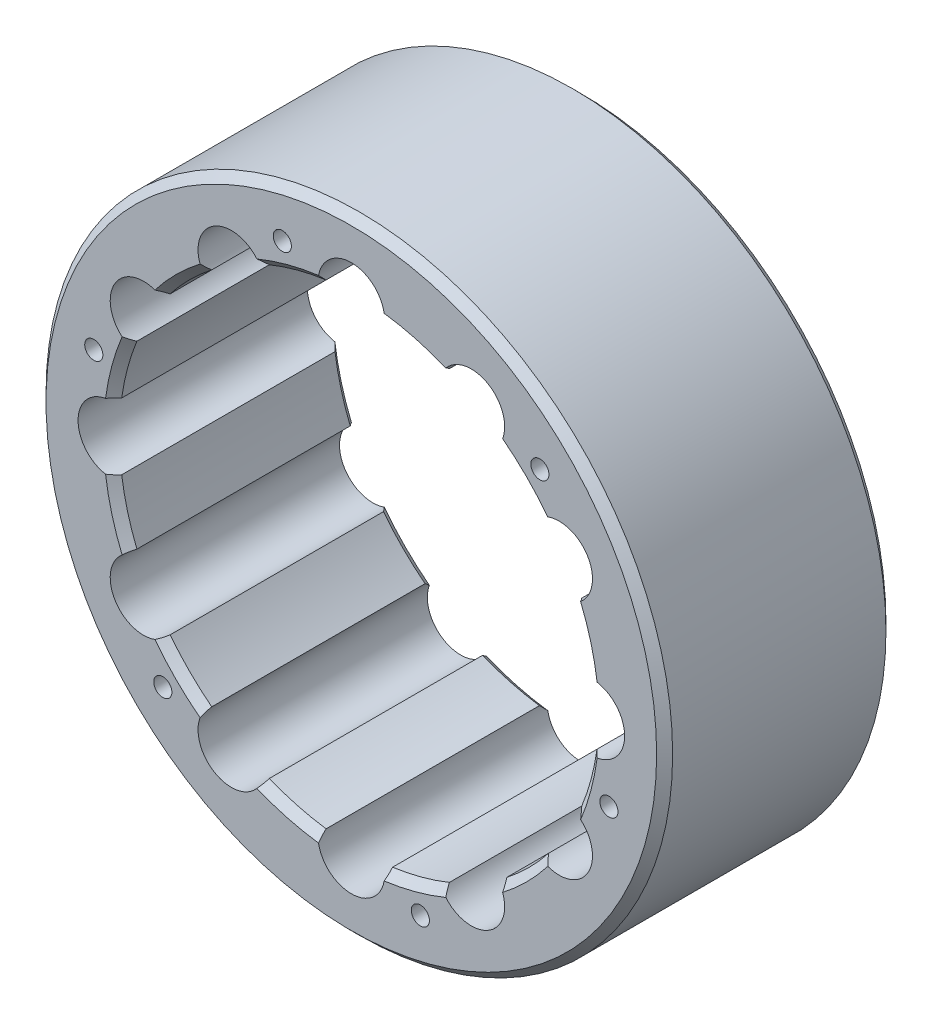
SolidWorks part; units mm, degrees
ref_plane "前视" through (0, 0, 0) normal (0, 0, 1) x (1, 0, 0)
ref_plane "上视" through (0, 0, 0) normal (0, 1, 0) x (1, 0, 0)
ref_plane "右视" through (0, 0, 0) normal (1, 0, 0) x (0, 0, -1)
sketch "草图1" plane through (0, 0, 0) normal (0, 0, 1) x (1, 0, 0)
  circle A0 centre (0, 0) radius 117.5
  circle A1 centre (0, 0) radius 90
  dimension "D1" = 235
  dimension "D2" = 180
extrude "凸台-拉伸1" add sketch "草图1" along normal blind 86
chamfer "倒角1" distance 3 angle 45 4 edges at (90, 0, 0) (117.5, 0, 0) (117.5, 0, 86) (90, 0, 86)
sketch "草图2" plane through (0, 0, 86) normal (0, 0, 1) x (1, 0, 0)
  line L0 (0, 0) -> (0, 203.5148) construction
  circle A0 centre (0, 90) radius 12.5
  circle A1 centre (0, 0) radius 90 construction
  circle A2 centre (45, 77.9423) radius 12.5
  circle A3 centre (77.9423, 45) radius 12.5
  circle A4 centre (90, 0) radius 12.5
  circle A5 centre (77.9423, -45) radius 12.5
  circle A6 centre (45, -77.9423) radius 12.5
  circle A7 centre (0, -90) radius 12.5
  circle A8 centre (-45, -77.9423) radius 12.5
  circle A9 centre (-77.9423, -45) radius 12.5
  circle A10 centre (-90, 0) radius 12.5
  circle A11 centre (-77.9423, 45) radius 12.5
  circle A12 centre (-45, 77.9423) radius 12.5
  circle A13 centre (0, 0) radius 90 construction
  dimension "D1" = 25
  dimension "D2" = 12
extrude "切除-拉伸1" cut sketch "草图2" against normal through all
sketch "草图3" plane through (0, 0, 86) normal (0, 0, 1) x (1, 0, 0)
  line L0 (0, 0) -> (-25.8819, 96.5926) construction
  circle A1 centre (0, 0) radius 100 construction
  circle A2 centre (-25.8819, 96.5926) radius 4
  circle A3 centre (70.7107, 70.7107) radius 4
  circle A4 centre (96.5926, -25.8819) radius 4
  circle A5 centre (25.8819, -96.5926) radius 4
  circle A6 centre (-70.7107, -70.7107) radius 4
  circle A7 centre (-96.5926, 25.8819) radius 4
  dimension "D1" = 200
  dimension "D2" = 8
  dimension "D3" = 6
sketch "草图4" plane through (0, 0, 0) normal (0, 0, -1) x (-1, 0, 0)
  circle A0 centre (70.7107, -70.7107) radius 4 construction
  circle A1 centre (-25.8819, -96.5926) radius 4 construction
  circle A2 centre (-96.5926, -25.8819) radius 4 construction
  circle A3 centre (-70.7107, 70.7107) radius 4 construction
  circle A4 centre (25.8819, 96.5926) radius 4 construction
  circle A5 centre (96.5926, 25.8819) radius 4 construction
  circle A6 centre (70.7107, -70.7107) radius 4
  circle A7 centre (-25.8819, -96.5926) radius 4
  circle A8 centre (-96.5926, -25.8819) radius 4
  circle A9 centre (-70.7107, 70.7107) radius 4
  circle A10 centre (25.8819, 96.5926) radius 4
  circle A11 centre (96.5926, 25.8819) radius 4
hole_wizard "M8 螺纹孔1" positions "3D草图1" profile "草图5" tap size "M8" standard "GB"
sketch3d "3D草图1"
  point P0 (-25.8819, 96.5926, 86)
  point P3 (70.7107, 70.7107, 86)
  point P6 (-96.5926, 25.8819, 86)
  point P9 (-70.7107, -70.7107, 86)
  point P12 (25.8819, -96.5926, 86)
  point P15 (96.5926, -25.8819, 86)
  point P18 (70.7107, 70.7107, 0)
  point P21 (-25.8819, 96.5926, 0)
  point P24 (-96.5926, 25.8819, 0)
  point P27 (-70.7107, -70.7107, 0)
  point P30 (25.8819, -96.5926, 0)
  point P33 (96.5926, -25.8819, 0)
sketch "草图5" plane through (-25.8819, 96.5926, 86) normal (1, 0, 0) x (0, -1, 0)
  line L0 (0, 0) -> (0, 16.0429)
  line L1 (0, 16.0429) -> (3.4, 14)
  line L2 (3.4, 14) -> (3.4, 0)
  line L5 (3.4, 0) -> (0, 0)
  line L10 (0, 16.0429) -> (-3.4, 14) construction
  line L11 (0, -6.35) -> (0, 107.95) construction
  dimension "螺纹孔钻头直径" = 6.8
  dimension "螺纹孔钻头深度" = 14
  dimension "导头角度" = 118
cosmetic thread "孔螺蚊线13" parameters "D1"=16, "D2"=8
cosmetic thread "孔螺蚊线14" parameters "D1"=16, "D2"=8
cosmetic thread "孔螺蚊线15" parameters "D1"=16, "D2"=8
cosmetic thread "孔螺蚊线16" parameters "D1"=16, "D2"=8
cosmetic thread "孔螺蚊线17" parameters "D1"=16, "D2"=8
cosmetic thread "孔螺蚊线18" parameters "D1"=16, "D2"=8
cosmetic thread "孔螺蚊线19" parameters "D1"=16, "D2"=8
cosmetic thread "孔螺蚊线20" parameters "D1"=16, "D2"=8
cosmetic thread "孔螺蚊线21" parameters "D1"=16, "D2"=8
cosmetic thread "孔螺蚊线22" parameters "D1"=16, "D2"=8
cosmetic thread "孔螺蚊线23" parameters "D1"=16, "D2"=8
cosmetic thread "孔螺蚊线24" parameters "D1"=16, "D2"=8
scale "缩放比例1" scale about origin uniform scaling yes scale factor 0.2
